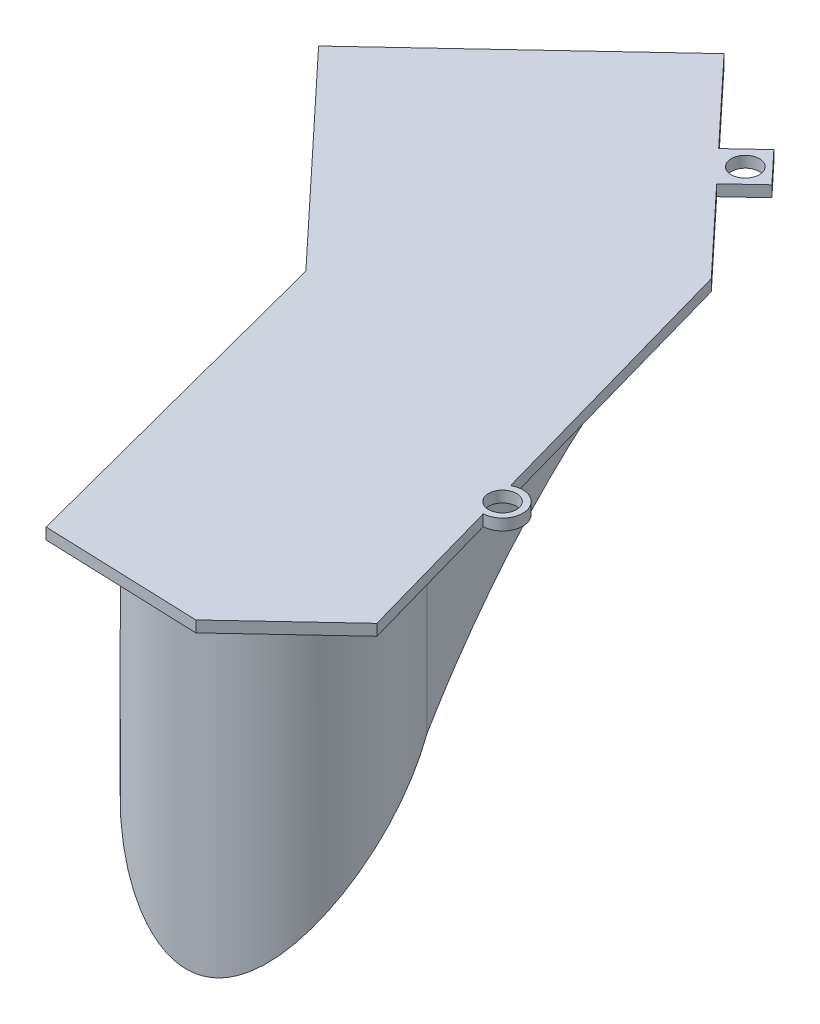
SolidWorks part; units mm, degrees
ref_plane "Front Plane" through (0, 0, 0) normal (0, 0, 1) x (1, 0, 0)
ref_plane "Top Plane" through (0, 0, 0) normal (0, 1, 0) x (1, 0, 0)
ref_plane "Right Plane" through (0, 0, 0) normal (1, 0, 0) x (0, 0, -1)
sketch "Sketch1" plane through (0, 0, 0) normal (0, 1, 0) x (1, 0, 0)
  line L0 (70.0909, -61.6651) -> (85.7747, -4.3259) construction
  line L1 (89.5435, 90.0426) -> (71.5159, 109.2898) construction
  line L2 (46.8036, 135.674) -> (-0.6673, 91.2112) construction
  line L3 (85.7747, -4.3259) -> (41.4911, 59.2395) construction
  line L4 (89.5435, 90.0426) -> (107.4179, 26.6464) construction
  line L5 (119.3174, -15.558) -> (70.0909, -61.6651) construction
  line L6 (70.0909, -61.6651) -> (42.0726, 45.5798) construction
  line L7 (119.3174, -15.558) -> (109.8503, 18.0194)
  line L8 (89.5435, 90.0426) -> (71.5159, 109.2898)
  line L9 (46.8036, 135.674) -> (-0.6673, 91.2112)
  line L10 (-0.6673, 91.2112) -> (42.0726, 45.5798)
  line L11 (42.0726, 45.5798) -> (70.0909, -61.6651)
  line L12 (119.3174, -15.558) -> (70.0909, -61.6651)
  line L13 (109.8503, 18.0194) -> (119.3174, -15.558) construction
  line L14 (107.4179, 26.6464) -> (89.5435, 90.0426)
  line L15 (41.4911, 59.2395) -> (73.0997, 90.8519) construction
  line L16 (94.7041, -38.6116) -> (85.7747, -4.3259) construction
  line L17 (70.0909, -61.6651) -> (56.995, -11.5385) construction
  line L18 (74.6359, 112.1934) -> (74.6269, 112.2037) construction
  line L19 (56.995, -11.5385) -> (85.7747, -4.3259) construction
  line L20 (68.1829, 119.5661) -> (64.8312, 116.4268) construction
  line L21 (71.2971, 122.2918) -> (71.4145, 122.3946) construction
  line L22 (56.995, -11.5385) -> (61.1367, -10.5005) construction
  line L23 (61.1367, -10.5005) -> (46.3531, 47.3429) construction
  line L24 (77.9786, 115.343) -> (71.5159, 109.2898)
  line L25 (77.9786, 115.343) -> (71.2939, 122.48)
  line L26 (71.2939, 122.48) -> (64.8312, 116.4268)
  line L27 (23.0682, 113.4426) -> (25.8028, 110.0666) construction
  line L28 (25.8028, 110.0666) -> (46.8036, 129.7366) construction
  line L29 (64.8312, 116.4268) -> (46.8036, 135.674) construction
  line L30 (64.8312, 116.4268) -> (46.8036, 135.674)
  line L31 (71.2971, 122.2918) -> (71.2939, 122.48) construction
  line L32 (46.8036, 129.7366) -> (51.0775, 125.1736) construction
  line L33 (74.6269, 112.2037) -> (74.6359, 112.1934) construction
  line L34 (51.0775, 125.1736) -> (54.0398, 127.9483) construction
  line L35 (51.0775, 125.1736) -> (83.9823, 90.0426) construction
  line L36 (98.4807, 58.3445) -> (94.5691, 57.2417) construction
  line L37 (94.5691, 57.2417) -> (87.5734, 82.0537) construction
  line L38 (94.5691, 57.2417) -> (101.9576, 31.0364) construction
  line L39 (101.9576, 31.0364) -> (105.7683, 17.5209) construction
  line L40 (105.7683, 17.5209) -> (108.8445, 6.3018) construction
  line L41 (86.4108, 87.2002) -> (87.5734, 82.0537) construction
  line L42 (83.9823, 90.0426) -> (86.4108, 87.2002) construction
  line L43 (20.7027, 68.3955) -> (23.8625, 71.3552) construction
  line L44 (23.8625, 71.3552) -> (2.4926, 94.1709) construction
  line L45 (25.8028, 110.0666) -> (5.4549, 91.0081) construction
  line L46 (5.4549, 91.0081) -> (23.8625, 71.3552) construction
  line L47 (23.8625, 71.3552) -> (46.3531, 47.3429) construction
  line L48 (5.4549, 91.0081) -> (46.3531, 47.3429)
  line L49 (46.3531, 47.3429) -> (61.1367, -10.5005)
  line L50 (5.4549, 91.0081) -> (46.8036, 129.7366)
  line L51 (46.8036, 129.7366) -> (86.4108, 87.2002)
  line L52 (86.4108, 87.2002) -> (108.8445, 6.3018)
  arc A0 (109.8503, 18.0194) -> (107.4179, 26.6464) centre (109.6339, 22.6148) ccw
  circle A1 centre (71.405, 115.885) radius 3.175
  circle A2 centre (109.6339, 22.6148) radius 3.175
  circle A3 centre (85.7747, -4.3259) radius 25.4
  circle A4 centre (41.4911, 59.2395) radius 3.175
  circle A5 centre (73.0997, 90.8519) radius 3.175
  dimension "D1" = 6.35
  dimension "D2" = 6.35
  dimension "D5" = 50.8
  dimension "D8" = 6.35
  dimension "D3" = 59.4455
  dimension "D4" = 31.576
  dimension "D6" = 77.47
  dimension "D7" = 129.839
  dimension "D9" = 44.704
  dimension "D10" = 100.14
  dimension "D11" = 35.4294
  dimension "D12" = 4.2697
ref_plane "Plane1" through (0, 0, 0) normal (0, 1, 0) x (1, 0, 0)
sketch "Sketch2" plane through (0, 0, 0) normal (0, 1, 0) x (1, 0, 0)
  line L0 (85.7747, -4.3259) -> (56.995, -11.5385) construction
  line L1 (85.7747, -4.3259) -> (79.6001, 20.3122) construction
  line L2 (79.6001, 20.3122) -> (50.5743, 13.0379) construction
  line L3 (42.0726, 45.5798) -> (70.0909, -61.6651) construction
  line L4 (85.7747, -4.3259) -> (91.9494, -28.9639) construction
  line L5 (91.9494, -28.9639) -> (63.4158, -36.1149) construction
  line L6 (79.6001, 20.3122) -> (107.2501, 27.2417) construction
  line L7 (107.4179, 26.6464) -> (89.5435, 90.0426) construction
  circle A0 centre (85.7747, -4.3259) radius 25.4 construction
sketch "Sketch3" plane through (0, 0, 0) normal (0, 1, 0) x (1, 0, 0)
  line L0 (-0.6673, 91.2112) -> (42.0726, 45.5798)
  line L1 (42.0726, 45.5798) -> (62.9002, -34.1415)
  line L2 (98.1135, -35.4183) -> (119.3174, -15.558)
  line L3 (119.3174, -15.558) -> (109.8503, 18.0194)
  line L4 (119.3174, -15.558) -> (109.8503, 18.0194) construction
  line L6 (107.4179, 26.6464) -> (89.5435, 90.0426)
  line L7 (89.5435, 90.0426) -> (71.5159, 109.2898)
  line L8 (71.5159, 109.2898) -> (77.9786, 115.343)
  line L9 (77.9786, 115.343) -> (71.2939, 122.48)
  line L10 (71.2939, 122.48) -> (64.8312, 116.4268)
  line L11 (64.8312, 116.4268) -> (46.8036, 135.674)
  line L12 (46.8036, 135.674) -> (-0.6673, 91.2112)
  line L13 (107.4179, 26.6464) -> (107.8199, 25.2206) construction
  line L14 (109.4483, 19.4453) -> (107.8199, 25.2206) construction
  line L15 (109.4483, 19.4453) -> (109.8503, 18.0194) construction
  line L16 (109.6339, 22.6148) -> (108.6341, 22.3329) construction
  line L17 (109.6339, 22.6148) -> (112.6898, 23.4764) construction
  line L18 (112.6898, 23.4764) -> (114.0618, 23.8633) construction
  line L19 (62.9002, -34.1415) -> (98.1135, -35.4183) construction
  line L20 (62.9002, -34.1415) -> (98.1135, -35.4183)
  circle A0 centre (71.405, 115.885) radius 3.175
  circle A1 centre (109.6339, 22.6148) radius 3.175
  arc A2 (109.8503, 18.0194) -> (107.4179, 26.6464) centre (109.6339, 22.6148) ccw
extrude "Boss-Extrude1" add sketch "Sketch3" along normal blind 2.54
sketch "Sketch4" plane through (0, 2.54, 0) normal (0, 1, 0) x (1, 0, 0)
  line L0 (46.8036, 129.7366) -> (5.4549, 91.0081)
  line L1 (5.4549, 91.0081) -> (46.3531, 47.3429)
  line L2 (46.3531, 47.3429) -> (61.1367, -10.5005)
  line L3 (46.8036, 129.7366) -> (86.4108, 87.2002)
  line L4 (86.4108, 87.2002) -> (108.8445, 6.3018)
  arc A0 (61.1367, -10.5005) -> (108.8445, 6.3018) centre (85.7747, -4.3259) ccw
ref_plane "Plane2" through (0, 2.54, 0) normal (0, 1, 0) x (1, 0, 0)
sketch "Sketch10" plane through (0, 2.54, 0) normal (0, 1, 0) x (1, 0, 0)
  line L0 (62.814, -33.8814) -> (98.1739, -35.3377) construction
  line L1 (98.1739, -35.3377) -> (119.31, -15.5526) construction
  line L2 (119.31, -15.5526) -> (110.5, 18.2067) construction
  line L3 (110.5, 18.2067) -> (51.689, 8.7483) construction
  line L5 (51.689, 8.7483) -> (62.814, -33.8814) construction
  line L6 (85.7054, -4.0783) -> (61.117, -10.4951) construction
  line L8 (61.117, -10.4951) -> (56.9972, -11.5702) construction
  line L9 (85.7054, -4.0783) -> (92.1192, -28.6552) construction
  dimension "D1" = 44.0575
  dimension "D2" = 106.985
ref_plane "Plane3" through (50.5316, 0, -13.2016) normal (-0.9675, 0, 0.2528) x (0.2528, 0, 0.9675)
sketch "Sketch11" plane through (0, 2.54, 0) normal (0, 1, 0) x (1, 0, 0)
  line L0 (54.8471, 14.1087) -> (103.3114, 26.2546)
  line L1 (79.6001, 20.3122) -> (50.5743, 13.0379) construction
  line L2 (46.3531, 47.3429) -> (61.1367, -10.5005) construction
  line L3 (79.6001, 20.3122) -> (107.2501, 27.2417) construction
  line L4 (86.4108, 87.2002) -> (108.8445, 6.3018) construction
  line L5 (103.3114, 26.2546) -> (86.4108, 87.2002)
  line L7 (46.3531, 47.3429) -> (54.8471, 14.1087)
  line L8 (46.3531, 47.3429) -> (5.4549, 91.0081)
  line L9 (5.4549, 91.0081) -> (46.8036, 129.7366)
  line L10 (46.8036, 129.7366) -> (86.4108, 87.2002)
sketch "Sketch12" plane through (50.5316, 0, -13.2016) normal (-0.9675, 0, 0.2528) x (0.2528, 0, 0.9675)
  line L0 (25.9238, 53.34) -> (25.9238, 2.54) construction
  line L1 (51.2668, 2.54) -> (21.4156, 2.54) construction
  line L2 (25.9238, 53.34) -> (51.3238, 53.34) construction
  line L3 (51.3238, 53.34) -> (51.3238, 2.54) construction
  line L4 (0.5238, 2.54) -> (-33.4649, 2.54) construction
  line L5 (0.5238, 2.54) -> (0.5238, 53.34) construction
  line L6 (-33.4649, 2.54) -> (48.9322, 2.54) construction
  line L7 (0.5238, 53.34) -> (25.9238, 53.34) construction
  line L8 (51.3238, 53.34) -> (-21.2261, 2.54) construction
  line L9 (51.3238, 53.34) -> (51.3238, 65.1842) construction
  line L10 (51.3238, 65.1842) -> (34.0045, 65.1842) construction
  line L11 (34.0045, 65.1842) -> (-82.0496, 65.1842) construction
  line L12 (-33.4649, 2.54) -> (-33.4649, 55.1414) construction
  line L13 (0.5238, 53.34) -> (-33.4649, 53.34) construction
  line L14 (-33.4649, 53.34) -> (-72.7989, 53.34) construction
  line L15 (-72.7989, 53.34) -> (-125.6648, 53.34) construction
  line L16 (-125.6648, 53.34) -> (-125.6648, 2.54) construction
  line L17 (-125.6648, 2.54) -> (-33.4649, 2.54) construction
  line L18 (-21.2261, 2.54) -> (51.3238, 53.34)
  line L19 (51.3238, 53.34) -> (51.3238, 65.1842)
  line L20 (51.3238, 65.1842) -> (51.3238, 77.7269)
  line L21 (51.3238, 77.7269) -> (-129.8884, 77.7269)
  line L22 (-129.8884, 77.7269) -> (-128.6902, 2.54)
  line L23 (-128.6902, 2.54) -> (-21.2261, 2.54)
  dimension "D1" = 50.8
  dimension "D2" = 25.4
  dimension "D3" = 25.4
  dimension "D5" = 35
sketch "Sketch13" plane through (50.5316, 0, -13.2016) normal (-0.9675, 0, 0.2528) x (0.2528, 0, 0.9675)
  line L0 (51.3238, 2.54) -> (51.3238, 0) construction
  line L1 (59.0684, 0) -> (45.2128, 0) construction
  line L2 (65.3231, 7.9505) -> (65.3231, -42.8495) construction
  line L3 (51.3238, 0) -> (-9.2172, 0) construction
  line L4 (1.371, 0) -> (-64.4846, 0) construction
  line L5 (-9.2172, 0) -> (51.3238, -45.8408) construction
  line L6 (51.3238, -45.8408) -> (51.3238, 0) construction
extrude "Boss-Extrude2" add sketch "Sketch4" against normal blind 76.2
sketch "Sketch14" plane through (50.5316, 0, -13.2016) normal (-0.9675, 0, 0.2528) x (0.2528, 0, 0.9675)
  line L1 (-119.5863, -76.2) -> (-7.9647, -76.2)
  line L2 (-119.5863, -76.2) -> (-119.5863, 0)
  line L3 (-119.5863, 0) -> (-52.8162, 0)
  line L6 (52.7626, -76.2) -> (-7.9647, -76.2)
  line L7 (-52.8162, 2.54) -> (-52.8162, 0) construction
  line L8 (25.8668, 0) -> (51.2655, 0) construction
  line L9 (1.371, 0) -> (-64.4846, 0) construction
  arc A0 (52.7626, -76.2) -> (-52.8162, 0) centre (-74.0392, -140.6478) ccw
  dimension "D2" = 104.14
  dimension "D3" = 142.24
  dimension "D1" = 76.2
extrude "Cut-Extrude1" cut sketch "Sketch14" against normal through all both and the other way through all
